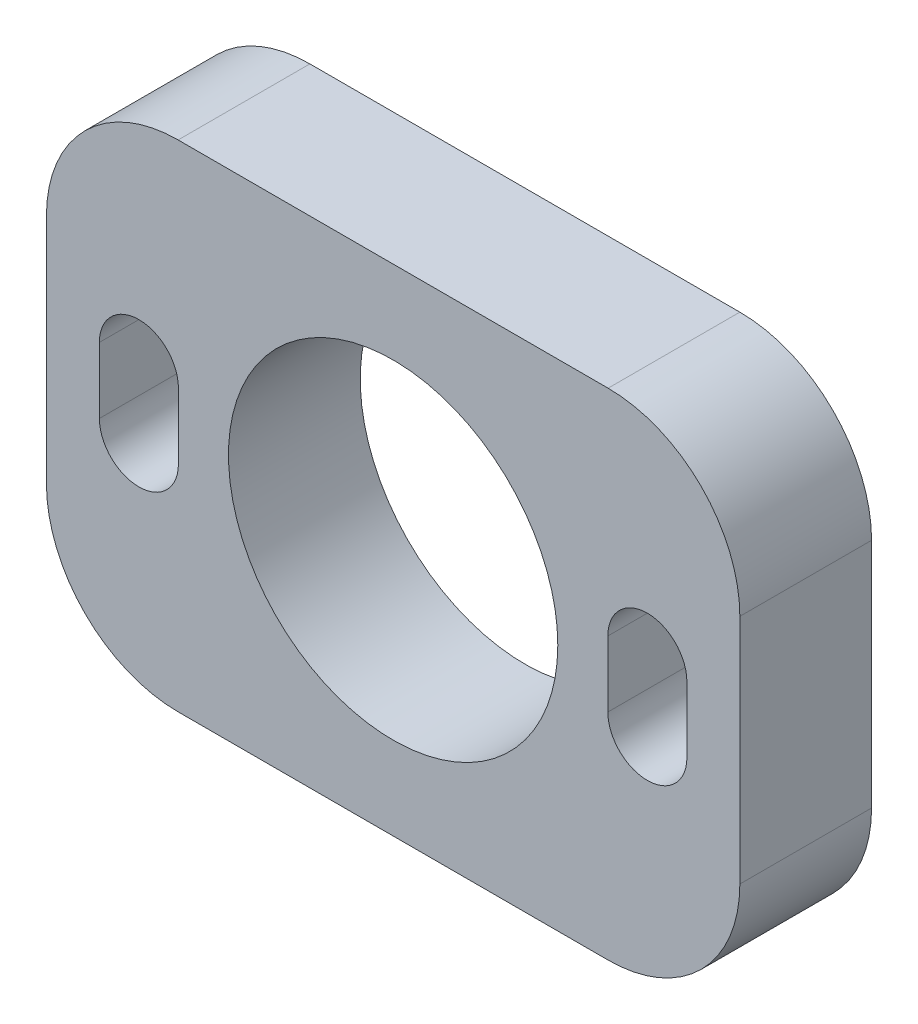
SolidWorks part; units mm, degrees
ref_plane "Front Plane" through (0, 0, 0) normal (0, 0, 1) x (1, 0, 0)
ref_plane "Top Plane" through (0, 0, 0) normal (0, 1, 0) x (1, 0, 0)
ref_plane "Right Plane" through (0, 0, 0) normal (1, 0, 0) x (0, 0, -1)
sketch "Sketch1" plane through (0, 0, -95.0394) normal (0, 0, 1) x (1, 0, 0)
  line L2 (15.3043, 36.6415) -> (15.3043, 12.7655) construction
  line L3 (15.3043, 32.641) -> (15.3043, 16.766) construction
  line L4 (1.1438, 26.291) -> (1.1438, 23.116) construction
  line L5 (4.9538, 26.291) -> (4.9538, 23.116) construction
  line L6 (15.3043, 36.6415) -> (15.3043, 12.7655)
  line L7 (15.3043, 32.641) -> (15.3043, 16.766)
  line L8 (25.6548, 26.291) -> (25.6548, 23.116) construction
  line L9 (-1.4089, 36.6415) -> (32.0175, 36.6415)
  line L10 (-1.4089, 36.6415) -> (-1.4089, 12.7655)
  line L11 (-1.4089, 12.7655) -> (32.0175, 12.7655)
  line L12 (32.0175, 36.6415) -> (32.0175, 12.7655)
  line L13 (29.4648, 26.291) -> (29.4648, 23.116) construction
  line L14 (1.1438, 26.291) -> (1.1438, 23.116)
  line L15 (4.9538, 26.291) -> (4.9538, 23.116)
  line L16 (25.6548, 26.291) -> (25.6548, 23.116)
  line L17 (29.4648, 26.291) -> (29.4648, 23.116)
  circle A2 centre (15.3043, 24.7035) radius 7.9375
  circle A3 centre (15.3043, 24.7035) radius 8.763
  arc A4 (4.9538, 26.291) -> (1.1438, 26.291) centre (3.0488, 26.291) ccw construction
  arc A5 (1.1438, 23.116) -> (4.9538, 23.116) centre (3.0488, 23.116) ccw construction
  arc A6 (25.6548, 23.116) -> (29.4648, 23.116) centre (27.5598, 23.116) ccw construction
  arc A7 (29.4648, 26.291) -> (25.6548, 26.291) centre (27.5598, 26.291) ccw construction
  arc A8 (4.9538, 26.291) -> (1.1438, 26.291) centre (3.0488, 26.291) ccw
  arc A9 (1.1438, 23.116) -> (4.9538, 23.116) centre (3.0488, 23.116) ccw
  arc A10 (25.6548, 23.116) -> (29.4648, 23.116) centre (27.5598, 23.116) ccw
  arc A11 (29.4648, 26.291) -> (25.6548, 26.291) centre (27.5598, 26.291) ccw
  point P0 (27.5598, 24.7035)
  point P2 (3.0488, 24.7035)
  dimension "D4" = 17.526
  dimension "D1" = 4.4577
  dimension "D2" = 4.4577
extrude "Boss-Extrude1" add sketch "Sketch1" along normal blind 6.35 contours A3 L6 L9 L10 L11 A9 L14 A8 L15 | A3 L6 L11 L12 L9 A11 L17 A10 L16 | L6 A3 A2 | L6 A3 A2
fillet "Fillet1" radius 6.35 4 edges at (32.0175, 36.6415, -91.8644) (32.0175, 12.7655, -91.8644) (-1.4089, 12.7655, -91.8644) (-1.4089, 36.6415, -91.8644)
equation "\"D2@Sketch1\"=\"D1@Sketch1\""
